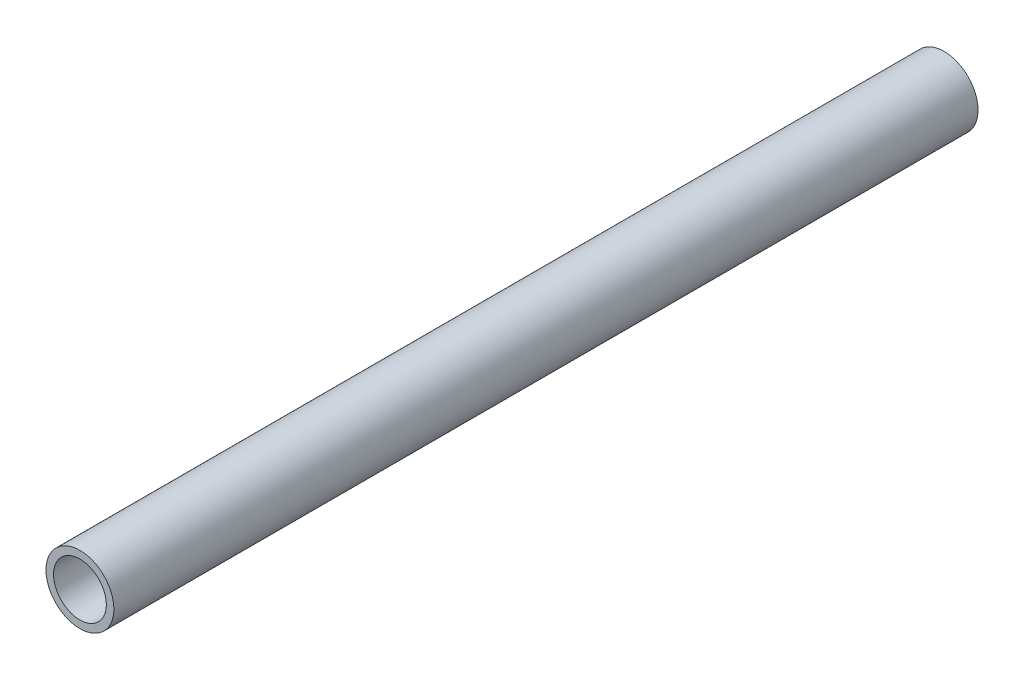
SolidWorks part; units mm, degrees
ref_plane "Front Plane" through (0, 0, 0) normal (0, 0, 1) x (1, 0, 0)
ref_plane "Top Plane" through (0, 0, 0) normal (0, 1, 0) x (1, 0, 0)
ref_plane "Right Plane" through (0, 0, 0) normal (1, 0, 0) x (0, 0, -1)
sketch "Sketch1" plane through (0, 0, 0) normal (0, 0, 1) x (1, 0, 0)
  circle A0 centre (0, 0) radius 9
  circle A1 centre (0, 0) radius 7
  dimension "D1" = 14
  dimension "D2" = 18
extrude "Boss-Extrude1" add sketch "Sketch1" along normal blind 229.2769
